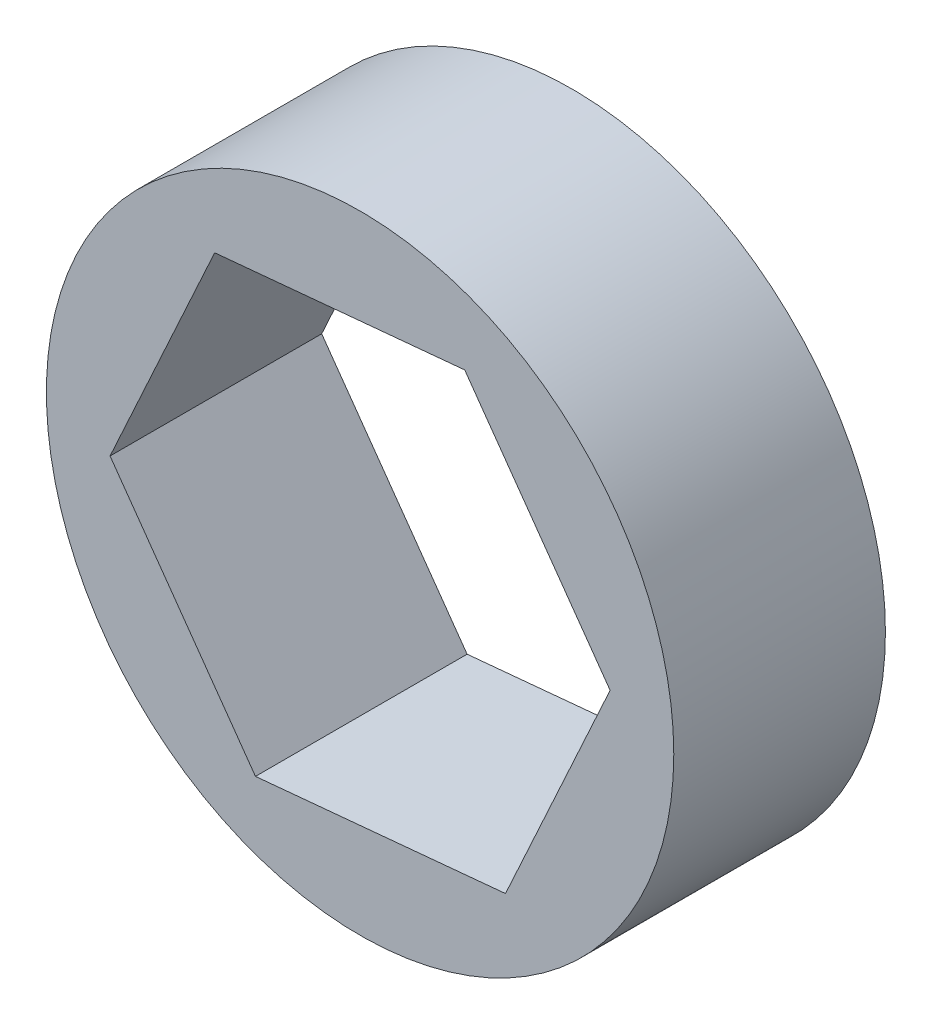
SolidWorks part; units mm, degrees
material "ABS"
ref_plane "Front Plane" through (0, 0, 0) normal (0, 0, 1) x (1, 0, 0)
ref_plane "Top Plane" through (0, 0, 0) normal (0, 1, 0) x (1, 0, 0)
ref_plane "Right Plane" through (0, 0, 0) normal (1, 0, 0) x (0, 0, -1)
sketch "Sketch1" plane through (0, 0, 0) normal (0, 0, 1) x (1, 0, 0)
  line L1 (-4.4153, 6.2174) -> (-7.592, -0.715)
  line L2 (-7.592, -0.715) -> (-3.1768, -6.9324)
  line L3 (-3.1768, -6.9324) -> (4.4153, -6.2174)
  line L4 (4.4153, -6.2174) -> (7.592, 0.715)
  line L5 (7.592, 0.715) -> (3.1768, 6.9324)
  line L6 (3.1768, 6.9324) -> (-4.4153, 6.2174)
  circle A0 centre (0, 0) radius 6.604 construction
  circle A1 centre (0, 0) radius 9.525
  dimension "D2" = 19.05
  dimension "D1" = 13.208
extrude "Boss-Extrude1" add sketch "Sketch1" along normal blind 6.4262
